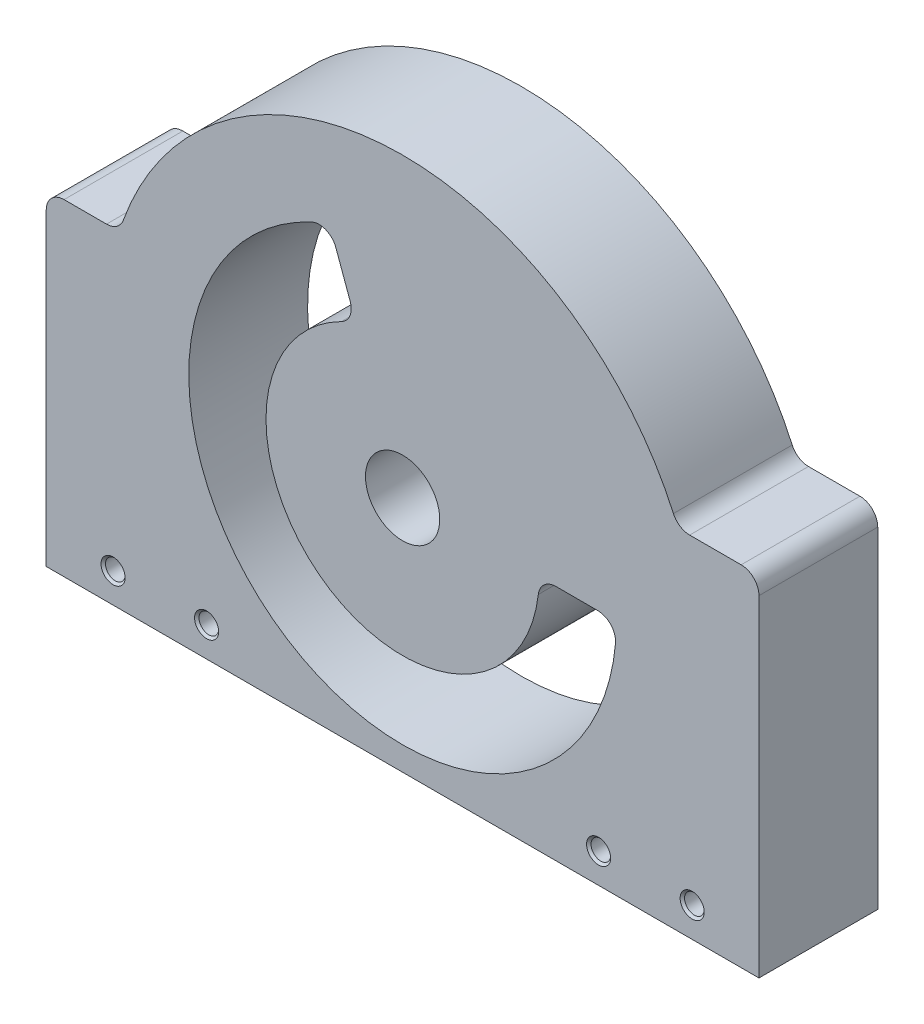
SolidWorks part; units mm, degrees
material "3.3547 (EN-AW 5083)"
ref_plane "Ebene vorne" through (0, 0, 0) normal (0, 0, 1) x (1, 0, 0)
ref_plane "Ebene oben" through (0, 0, 0) normal (0, 1, 0) x (1, 0, 0)
ref_plane "Ebene rechts" through (0, 0, 0) normal (1, 0, 0) x (0, 0, -1)
sketch "Skizze1" plane through (0, 0, 0) normal (0, 0, 1) x (1, 0, 0)
  line L0 (0, 0) -> (120, 0)
  line L1 (60, 0) -> (60, 111.8449) construction
  line L5 (0, 55) -> (0, 0)
  line L7 (120, 58.75) -> (120, 0)
  line L8 (120, 58.75) -> (106.3512, 58.75)
  line L9 (12.303, 55) -> (0, 55)
  circle A1 centre (60, 40) radius 6.25
  arc A2 (106.3512, 58.75) -> (12.303, 55) centre (60, 40) ccw
  dimension "D1" = 120
  dimension "D2" = 40
  dimension "D3" = 55
  dimension "D4" = 50
  dimension "D5" = 12.5
extrude "Aufsatz-Linear austragen1" add sketch "Skizze1" along normal blind 20
sketch "Skizze4" plane through (0, 0, 0) normal (0, 0, -1) x (-1, 0, 0)
  circle A0 centre (-60, 40) radius 13
extrude "Schnitt-Linear austragen2" cut sketch "Skizze4" against normal blind 8
sketch "Skizze5" plane through (0, 0, 0) normal (0, 0, -1) x (-1, 0, 0)
  line L0 (-120, 40) -> (0, 40) construction
  line L1 (-120, 0) -> (-120, 58.75) construction
  line L2 (0, 55) -> (0, 0) construction
  line L3 (-60, 40) -> (-107.62, 40) construction
  line L4 (-60, 40) -> (-44.2151, 83.3686) construction
  line L5 (-96, 40) -> (-83, 40)
  line L6 (-52.1335, 61.6129) -> (-47.6873, 73.8289)
  arc A0 (-83, 40) -> (-52.1335, 61.6129) centre (-60, 40) ccw
  arc A1 (-96, 40) -> (-47.6873, 73.8289) centre (-60, 40) ccw
  dimension "D1" = 0
  dimension "D2" = 70
extrude "Schnitt-Linear austragen3" cut sketch "Skizze5" against normal blind 34.3
fillet "Verrundung1" radius 3 4 edges at (52.1335, 61.6129, 10) (83, 40, 10) (96, 40, 10) (47.6873, 73.8289, 10)
fillet "Verrundung2" radius 3 4 edges at (120, 58.75, 10) (0, 55, 10) (12.303, 55, 10) (106.3512, 58.75, 10)
sketch "Skizze7" plane through (0, 0, 0) normal (0, 0, -1) x (-1, 0, 0)
  circle A0 centre (-72.0838, 50.8849) radius 1
  circle A1 centre (-49.1151, 52.0838) radius 1
  circle A2 centre (-70.8849, 27.9162) radius 1
  circle A3 centre (-47.9162, 29.1151) radius 1
extrude "Schnitt-Linear austragen5" cut sketch "Skizze7" against normal blind 15
hole_wizard "M4 Gewindebohrung3" positions "3D-Skizze3" profile "Skizze10" tap size "M4" standard "DIN"
sketch3d "3D-Skizze3"
  line L0 (72.0838, 50.8849, 15) -> (72.0838, 50.8849, 0) construction
  line L1 (49.1151, 52.0838, 15) -> (49.1151, 52.0838, 0) construction
  line L2 (47.9162, 29.1151, 15) -> (47.9162, 29.1151, 0) construction
  line L3 (70.8849, 27.9162, 15) -> (70.8849, 27.9162, 0) construction
  point P0 (72.0838, 50.8849, 0)
  point P4 (49.1151, 52.0838, 0)
  point P8 (47.9162, 29.1151, 0)
  point P12 (70.8849, 27.9162, 0)
sketch "Skizze10" plane through (72.0838, 50.8849, 0) normal (1, 0, 0) x (0, 1, 0)
  line L0 (0, 0) -> (0, 12.4914)
  line L1 (0, 12.4914) -> (1.65, 11.5)
  line L2 (1.65, 11.5) -> (1.65, 0.475)
  line L3 (1.65, 0.475) -> (2.125, 0)
  line L5 (2.125, 0) -> (0, 0)
  line L6 (-1.65, 0.475) -> (-2.125, 0) construction
  line L10 (0, 12.4914) -> (-1.65, 11.5) construction
  line L11 (0, -6.35) -> (0, 107.95) construction
  dimension "Bohrerdurchmesser" = 3.3
  dimension "Bohrungstiefe" = 11.5
  dimension "Senkdurchmesser (Oben)" = 4.25
  dimension "Senkwinkel (Oben)" = 90
  dimension "Spitzenwinkel" = 118
cosmetic thread "Bohrungsgewinde13" parameters "D1"=8, "D2"=4
cosmetic thread "Bohrungsgewinde14" parameters "D1"=8, "D2"=4
cosmetic thread "Bohrungsgewinde15" parameters "D1"=8, "D2"=4
cosmetic thread "Bohrungsgewinde16" parameters "D1"=8, "D2"=4
sketch "Skizze11" plane through (0, 0, 20) normal (0, 0, 1) x (1, 0, 0)
  circle A0 centre (11.25, 5) radius 1.4635
  circle A1 centre (27, 5) radius 1.23
  circle A2 centre (93, 5) radius 1.2001
  circle A3 centre (108.75, 5) radius 0.6624
hole_wizard "M4 Gewindebohrung4" positions "3D-Skizze4" profile "Skizze12" tap size "M4" standard "DIN"
sketch3d "3D-Skizze4"
  point P0 (11.25, 5, 20)
  point P3 (27, 5, 20)
  point P6 (93, 5, 20)
  point P9 (108.75, 5, 20)
sketch "Skizze12" plane through (11.25, 5, 20) normal (1, 0, 0) x (0, -1, 0)
  line L0 (0, 0) -> (0, 12.4914)
  line L1 (0, 12.4914) -> (1.65, 11.5)
  line L2 (1.65, 11.5) -> (1.65, 0.375)
  line L3 (1.65, 0.375) -> (2.025, 0)
  line L5 (2.025, 0) -> (0, 0)
  line L6 (-1.65, 0.375) -> (-2.025, 0) construction
  line L10 (0, 12.4914) -> (-1.65, 11.5) construction
  line L11 (0, -6.35) -> (0, 107.95) construction
  dimension "Bohrerdurchmesser" = 3.3
  dimension "Bohrungstiefe" = 11.5
  dimension "Senkdurchmesser (Oben)" = 4.05
  dimension "Senkwinkel (Oben)" = 90
  dimension "Spitzenwinkel" = 118
cosmetic thread "Bohrungsgewinde17" parameters "D1"=8, "D2"=4
cosmetic thread "Bohrungsgewinde18" parameters "D1"=8, "D2"=4
cosmetic thread "Bohrungsgewinde19" parameters "D1"=8, "D2"=4
cosmetic thread "Bohrungsgewinde20" parameters "D1"=8, "D2"=4
